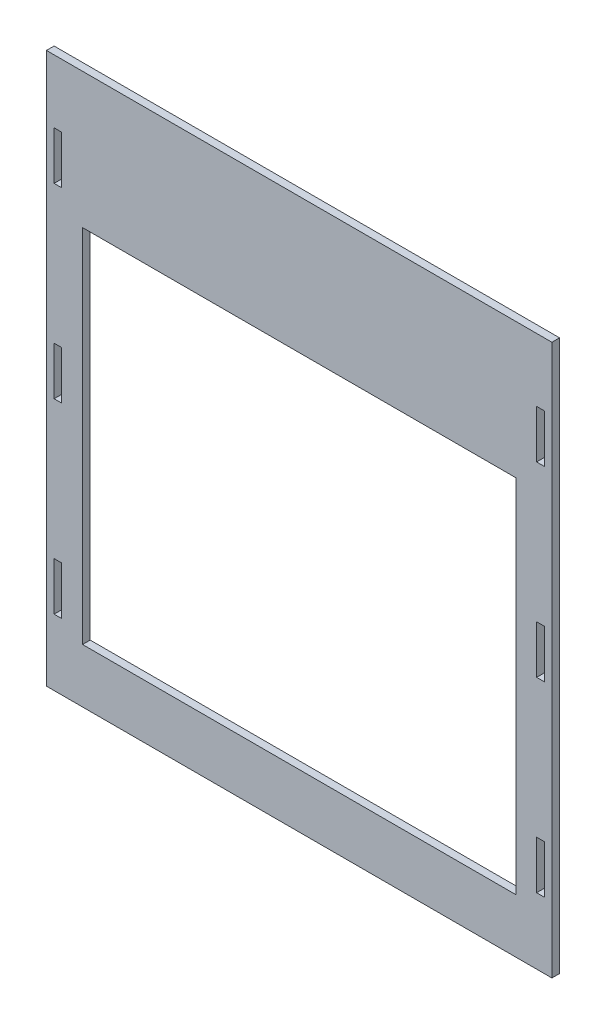
SolidWorks part; units mm, degrees
ref_plane "Front Plane" through (0, 0, 0) normal (0, 0, 1) x (1, 0, 0)
ref_plane "Top Plane" through (0, 0, 0) normal (0, 1, 0) x (1, 0, 0)
ref_plane "Right Plane" through (0, 0, 0) normal (1, 0, 0) x (0, 0, -1)
sketch "Sketch1" plane through (0, 0, 0) normal (0, 0, 1) x (1, 0, 0)
  line L0 (6.35, 405) -> (6.35, 365)
  line L1 (0, 0) -> (420, 0)
  line L2 (0, 0) -> (0, 457.5)
  line L3 (0, 457.5) -> (6.35, 457.5)
  line L4 (420, 0) -> (420, 457.5)
  line L6 (12.7, 365) -> (12.7, 405)
  line L10 (12.7, 457.5) -> (407.3, 457.5)
  line L11 (413.65, 457.5) -> (420, 457.5)
  line L12 (407.3, 457.5) -> (413.65, 457.5)
  line L17 (407.3, 405) -> (413.65, 405)
  line L18 (413.65, 405) -> (413.65, 365)
  line L19 (413.65, 365) -> (407.3, 365)
  line L20 (407.3, 365) -> (407.3, 405)
  line L21 (6.35, 405) -> (12.7, 405)
  line L22 (6.35, 365) -> (12.7, 365)
  line L23 (6.35, 457.5) -> (12.7, 457.5)
  line L24 (12.7, 250) -> (12.7, 210)
  line L25 (12.7, 210) -> (6.35, 210)
  line L26 (6.35, 210) -> (6.35, 250)
  line L27 (6.35, 250) -> (12.7, 250)
  line L28 (413.65, 250) -> (413.65, 210)
  line L29 (413.65, 210) -> (407.3, 210)
  line L30 (407.3, 210) -> (407.3, 250)
  line L31 (407.3, 250) -> (413.65, 250)
  line L32 (413.65, 95) -> (413.65, 55)
  line L33 (413.65, 55) -> (407.3, 55)
  line L34 (407.3, 55) -> (407.3, 95)
  line L35 (407.3, 95) -> (413.65, 95)
  line L36 (12.7, 95) -> (12.7, 55)
  line L37 (12.7, 55) -> (6.35, 55)
  line L38 (6.35, 55) -> (6.35, 95)
  line L39 (6.35, 95) -> (12.7, 95)
  line L41 (30, 345) -> (390, 345)
  line L42 (30, 345) -> (30, 45)
  line L43 (30, 45) -> (390, 45)
  line L44 (390, 345) -> (390, 45)
  point P6 (9.525, 405)
  dimension "D1" = 457.5
  dimension "D2" = 420
  dimension "D3" = 40
  dimension "D4" = 52.5
  dimension "D5" = 6.35
  dimension "D6" = 6.35
  dimension "D7" = 52.5
  dimension "D8" = 55
  dimension "D9" = 30
  dimension "D10" = 30
  dimension "D11" = 45
  dimension "D12" = 55
  dimension "D13" = 250
  dimension "D14" = 250
  dimension "D15" = 300
extrude "Boss-Extrude1" add sketch "Sketch1" along normal blind 6.35
